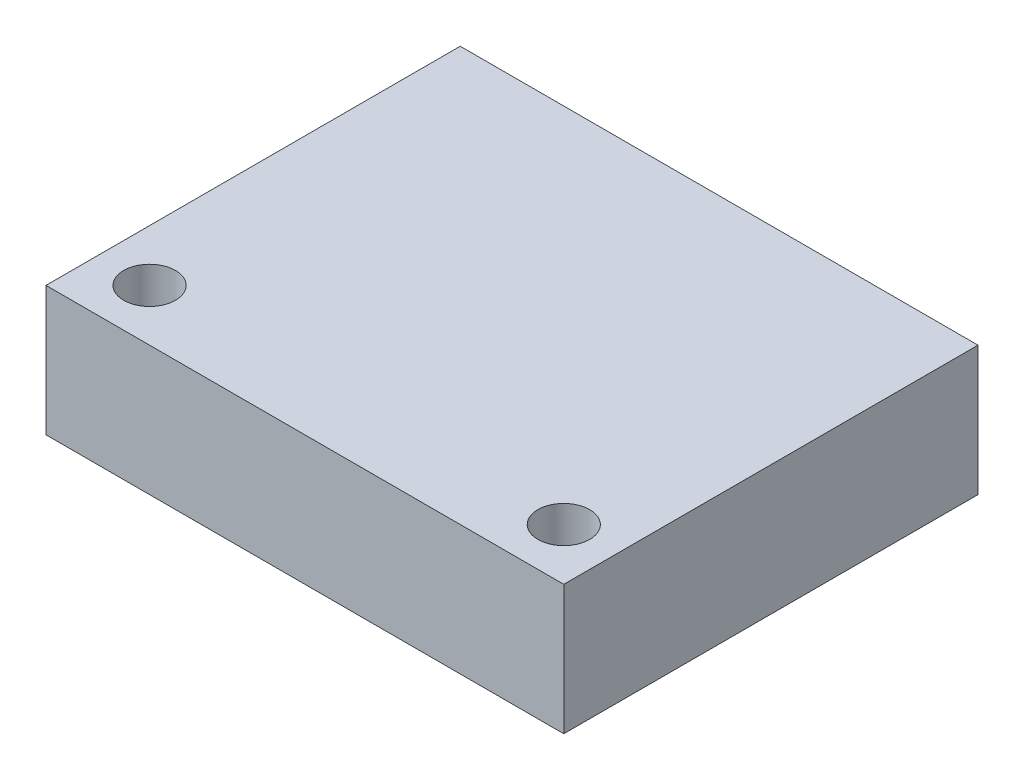
SolidWorks part; units mm, degrees
ref_plane "Piano frontale" through (0, 0, 0) normal (0, 0, 1) x (1, 0, 0)
ref_plane "Piano superiore" through (0, 0, 0) normal (0, 1, 0) x (1, 0, 0)
ref_plane "Piano destro" through (0, 0, 0) normal (1, 0, 0) x (0, 0, -1)
sketch "Schizzo1" plane through (0, 0, 0) normal (0, 1, 0) x (1, 0, 0)
  line L1 (-10, -8) -> (10, -8)
  line L2 (-10, -8) -> (-10, 8)
  line L3 (-10, 8) -> (10, 8)
  line L4 (10, -8) -> (10, 8)
  line L5 (-10, -8) -> (10, 8) construction
  line L6 (-10, 8) -> (10, -8) construction
  point P0 (0, 0)
  dimension "D1" = 20
  dimension "D2" = 16
extrude "Estrusione-Estrusione1" add sketch "Schizzo1" along normal blind 5
sketch "Schizzo2" plane through (0, 5, 0) normal (0, 1, 0) x (1, 0, 0)
  line L0 (-10, -8) -> (10, -8) construction
  line L1 (-10, 8) -> (-10, -8) construction
  line L3 (10, -8) -> (10, 8) construction
  circle A0 centre (-8, -6) radius 1
  circle A1 centre (8, -6) radius 1
  dimension "D1" = 2
  dimension "D2" = 2
  dimension "D3" = 2
  dimension "D4" = 2
  dimension "D5" = 2
  dimension "D6" = 2
extrude "Taglio-Estrusione1" cut sketch "Schizzo2" against normal blind 5
